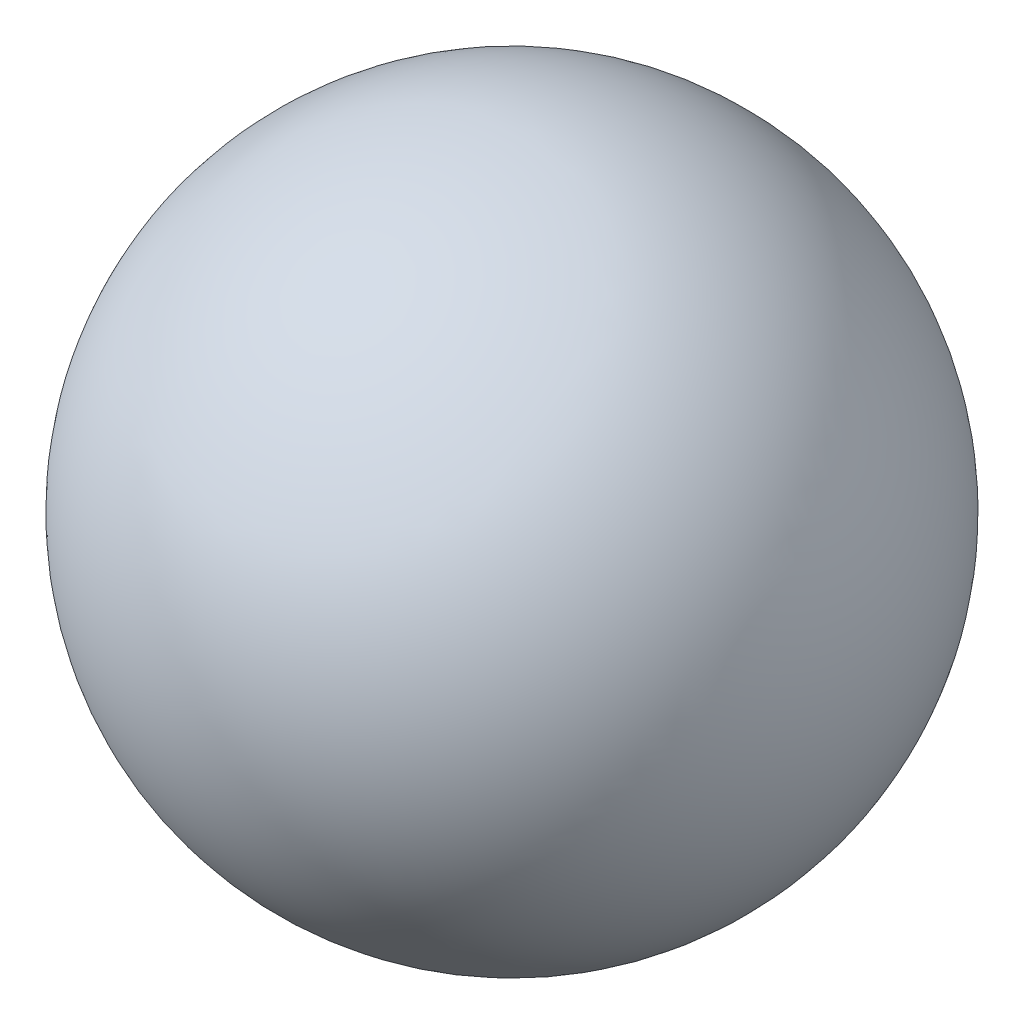
SolidWorks part; units mm, degrees
material "PLA"
ref_plane "Front Plane" through (0, 0, 0) normal (0, 0, 1) x (1, 0, 0)
ref_plane "Top Plane" through (0, 0, 0) normal (0, 1, 0) x (1, 0, 0)
ref_plane "Right Plane" through (0, 0, 0) normal (1, 0, 0) x (0, 0, -1)
sketch "Sketch1" plane through (0, 0, 0) normal (0, 0, 1) x (1, 0, 0)
  line L0 (0, 0) -> (30, 0)
  arc A0 (30, 0) -> (0, 0) centre (15, 0) ccw
  dimension "D1" = 30
revolve "Revolve1" add sketch "Sketch1" angle 360 about L0
